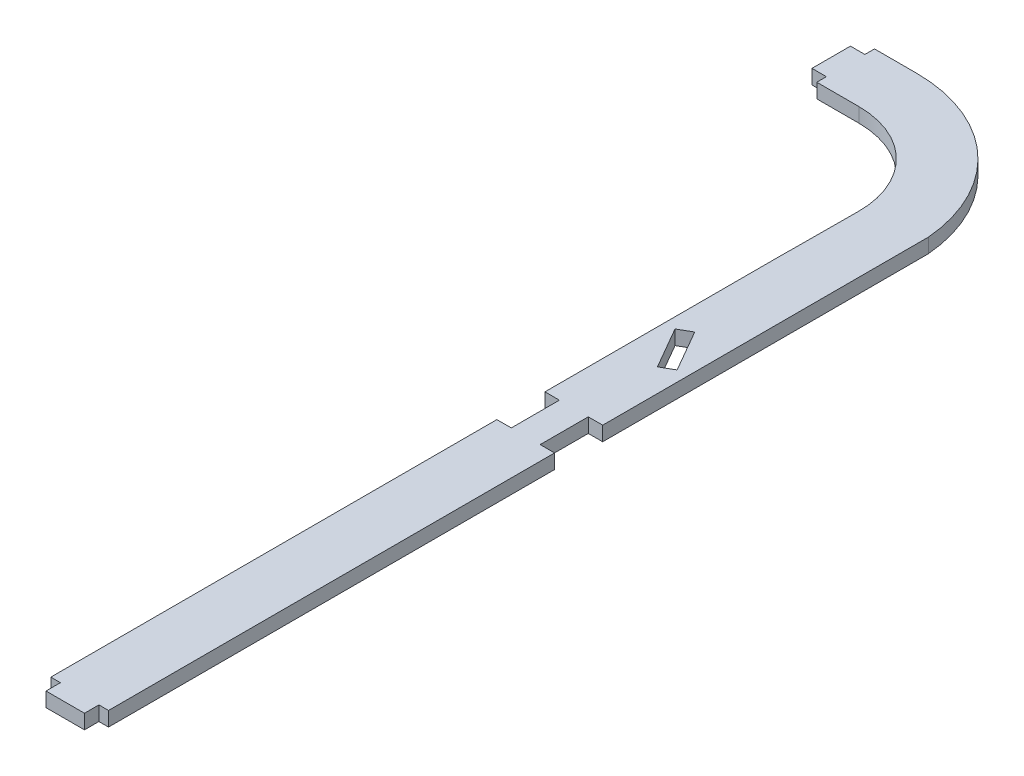
SolidWorks part; units mm, degrees
ref_plane "Alzado" through (0, 0, 0) normal (0, 0, 1) x (1, 0, 0)
ref_plane "Planta" through (0, 0, 0) normal (0, 1, 0) x (1, 0, 0)
ref_plane "Vista lateral" through (0, 0, 0) normal (1, 0, 0) x (0, 0, -1)
sketch "Croquis1" plane through (0, 0, 0) normal (0, 1, 0) x (1, 0, 0)
  line L0 (37.51, 4) -> (34.51, 4)
  line L1 (34.51, 0) -> (34.51, 8)
  line L2 (34.51, 8) -> (37.51, 8)
  line L3 (37.51, 8) -> (37.51, 10)
  line L4 (77, -188.737) -> (77, -96) construction
  line L5 (72.5, 3.893) -> (72.5, -188.737) construction
  line L6 (65, -38.5334) -> (65.107, -20.8557)
  line L7 (37.51, 10) -> (46.2513, 10)
  line L8 (37.51, -2) -> (46.2513, -2)
  line L9 (37.51, 0) -> (37.51, -2)
  line L10 (65, -188.737) -> (67, -188.737)
  line L11 (77, -188.737) -> (77, -96)
  line L12 (75, -191.737) -> (67, -191.737)
  line L13 (67, -191.737) -> (67, -188.737)
  line L14 (34.51, 0) -> (37.51, 0)
  line L15 (75, -191.737) -> (75, -188.737)
  line L16 (75, -188.737) -> (77, -188.737)
  line L17 (65, -117.737) -> (65, -188.737)
  line L18 (77, 4) -> (37.51, 4) construction
  line L19 (71, 3.893) -> (46.2513, -20.8557) construction
  line L20 (65, -117.737) -> (65, -96)
  line L21 (71, -105.737) -> (71, 3.893) construction
  line L22 (77, -188.737) -> (77, -96)
  line L23 (77, -38.5334) -> (77.107, -20.8557)
  line L24 (77, 4) -> (77, -64.74)
  line L25 (77, -64.74) -> (65, -64.74) construction
  line L26 (72.299, -63.99) -> (69.701, -65.49) construction
  line L27 (73.5, -69.0701) -> (68.5, -60.4099) construction
  line L28 (69.799, -59.6599) -> (67.201, -61.1599)
  line L29 (67.201, -61.1599) -> (72.201, -69.8201)
  line L30 (74.799, -68.3201) -> (72.201, -69.8201)
  line L31 (69.799, -59.6599) -> (74.799, -68.3201)
  line L32 (77, 4) -> (77, -86)
  line L34 (77, -86) -> (74, -86)
  line L35 (74, -86) -> (74, -96)
  line L36 (74, -96) -> (77, -96)
  line L37 (68, -96) -> (65, -96)
  line L38 (68, -86) -> (68, -96)
  line L39 (65, -86) -> (68, -86)
  line L40 (65, -86) -> (65, -38.5334)
  line L41 (77, -86) -> (77, 4) construction
  line L42 (77, -86) -> (77, -38.5334)
  line L43 (77, -86) -> (77, -38.5334)
  arc A0 (65.1056, -21.0838) -> (46.2513, -2) centre (46.2513, -20.8557) ccw
  arc A2 (77, -23.4225) -> (46.2513, 10) centre (46.2513, -20.8557) ccw
  point P39 (71, -64.74)
  dimension "D1" = 3
  dimension "D2" = 4
  dimension "D3" = 39.49
  dimension "D4" = 35
  dimension "D5" = 192.63
  dimension "D6" = 2
  dimension "D7" = 68.74
  dimension "D8" = 30
  dimension "D10" = 1.5
  dimension "D11" = 5
  dimension "D13" = 3
  dimension "D14" = 10
extrude "Saliente-Extruir1" add sketch "Croquis1" along normal blind 3
